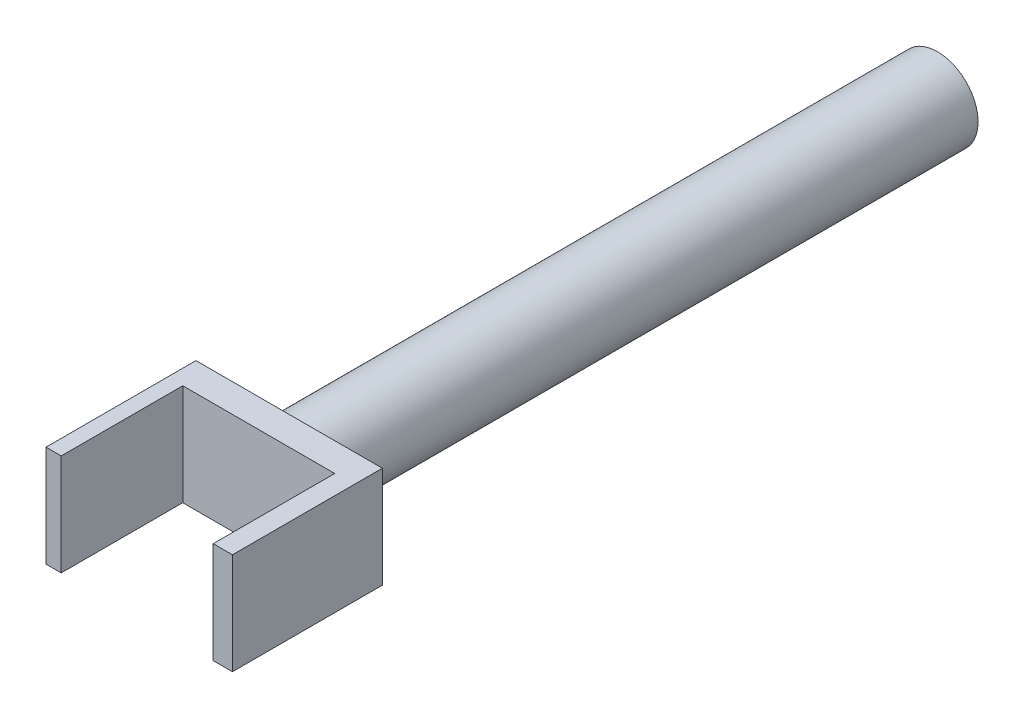
SolidWorks part; units mm, degrees
ref_plane "Front Plane" through (0, 0, 0) normal (0, 0, 1) x (1, 0, 0)
ref_plane "Top Plane" through (0, 0, 0) normal (0, 1, 0) x (1, 0, 0)
ref_plane "Right Plane" through (0, 0, 0) normal (1, 0, 0) x (0, 0, -1)
sketch "Sketch1" plane through (0, 0, 0) normal (0, 0, 1) x (1, 0, 0)
  line L1 (-23, 12.5) -> (23, 12.5)
  line L2 (-23, 12.5) -> (-23, -12.5)
  line L3 (-23, -12.5) -> (23, -12.5)
  line L4 (23, 12.5) -> (23, -12.5)
  line L5 (-23, 7.5) -> (-23, -7.5) construction
  line L6 (23, -12.5) -> (20, -12.5) construction
  line L7 (23, 7.5) -> (23, -7.5) construction
  point P6 (-23, 0)
  point P8 (-23, 0)
extrude "Boss-Extrude1" add sketch "Sketch1" against normal up to surface (37 mm away)
sketch "Sketch2" plane through (0, 0, -37) normal (0, 0, -1) x (-1, 0, 0)
  arc A0 (-3.2143, 9.4693) -> (3.2143, 9.4693) centre (0, 0) ccw construction
  circle A1 centre (0, 0) radius 10
extrude "Boss-Extrude2" add sketch "Sketch2" along normal up to surface (160 mm away)
sketch "Sketch3" plane through (0, 0, 0) normal (0, 0, 1) x (1, 0, 0)
  line L0 (18.25, 18.4) -> (-19.25, 18.4)
  line L1 (-19.25, 18.4) -> (-19.25, -18.4)
  line L2 (-19.25, -18.4) -> (18.25, -18.4)
  line L3 (18.25, -18.4) -> (18.25, 18.4)
  line L4 (-18.25, -17.4) -> (17.25, -17.4)
  line L5 (17.25, -17.4) -> (17.25, 17.4)
  line L6 (17.25, 17.4) -> (-18.25, 17.4)
  line L7 (-18.25, 17.4) -> (-18.25, -17.4)
  line L8 (-18.25, -17.4) -> (17.25, -17.4) construction
  line L9 (17.25, -17.4) -> (17.25, 17.4) construction
  line L10 (17.25, 17.4) -> (-18.25, 17.4) construction
  line L11 (-18.25, 17.4) -> (-18.25, -17.4) construction
  dimension "D1" = 0
  dimension "D2" = 1
extrude "Cut-Extrude1" cut sketch "Sketch3" against normal blind 30
